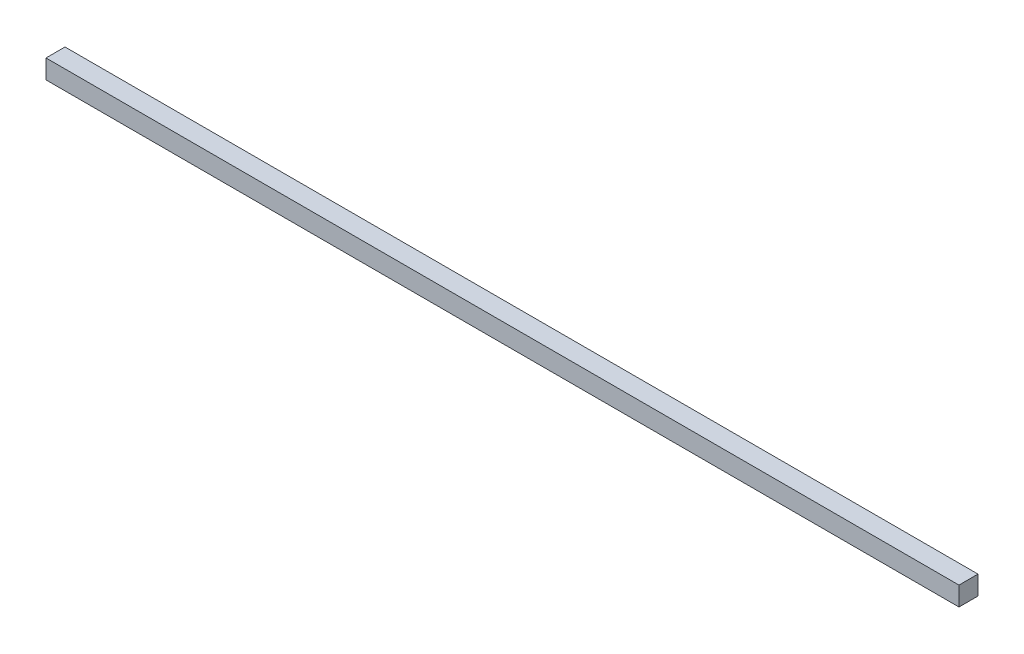
SolidWorks part; units mm, degrees
material "AISI 1035 Сталь (SS)"
ref_plane "Спереди" through (0, 0, 0) normal (0, 0, 1) x (1, 0, 0)
ref_plane "Сверху" through (0, 0, 0) normal (0, 1, 0) x (1, 0, 0)
ref_plane "Справа" through (0, 0, 0) normal (1, 0, 0) x (0, 0, -1)
sketch "Эскиз1" plane through (0, 0, 0) normal (0, 0, 1) x (1, 0, 0)
  line L1 (0, 57.9961) -> (1440, 57.9961)
  line L2 (0, 57.9961) -> (0, 27.9961)
  line L3 (0, 27.9961) -> (1440, 27.9961)
  line L4 (1440, 57.9961) -> (1440, 27.9961)
  dimension "D1" = 1440
  dimension "D2" = 30
extrude "Бобышка-Вытянуть1" add sketch "Эскиз1" along normal blind 30
